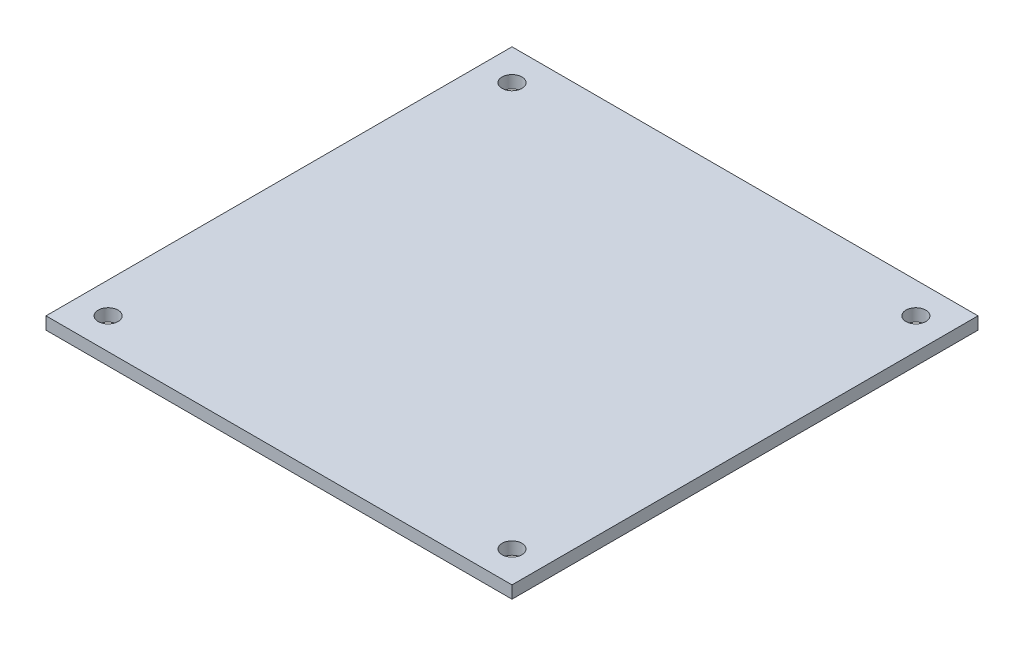
SolidWorks part; units mm, degrees
ref_plane "Front Plane" through (0, 0, 0) normal (0, 0, 1) x (1, 0, 0)
ref_plane "Top Plane" through (0, 0, 0) normal (0, 1, 0) x (1, 0, 0)
ref_plane "Right Plane" through (0, 0, 0) normal (1, 0, 0) x (0, 0, -1)
sketch "Sketch1" plane through (0, 0, 0) normal (0, 1, 0) x (1, 0, 0)
  line L0 (-37.5, 37.5) -> (-37.5, -37.5)
  line L1 (-32.5, 32.5) -> (32.5, 32.5)
  line L2 (-32.5, 32.5) -> (-32.5, -32.5)
  line L3 (-32.5, -32.5) -> (32.5, -32.5)
  line L4 (32.5, 32.5) -> (32.5, -32.5)
  line L5 (-32.5, 32.5) -> (32.5, -32.5) construction
  line L6 (-32.5, -32.5) -> (32.5, 32.5) construction
  line L7 (-37.5, -37.5) -> (37.5, -37.5)
  line L8 (37.5, 37.5) -> (37.5, -37.5)
  line L9 (-37.5, 37.5) -> (37.5, 37.5)
  circle A0 centre (-32.5, 32.5) radius 1.6
  circle A1 centre (-32.5, -32.5) radius 1.6
  circle A2 centre (32.5, 32.5) radius 1.6
  circle A3 centre (32.5, -32.5) radius 1.6
  point P0 (0, 0)
  dimension "D3" = 3.2
  dimension "D1" = 65
  dimension "D2" = 65
  dimension "D4" = 5
extrude "Boss-Extrude1" add sketch "Sketch1" along normal blind 2 contours A3 L4 A2 L1 A0 L2 A1 L3 | L9 L0 L7 L8 A3 L3 A1 L2 A0 L1 A2 L4
